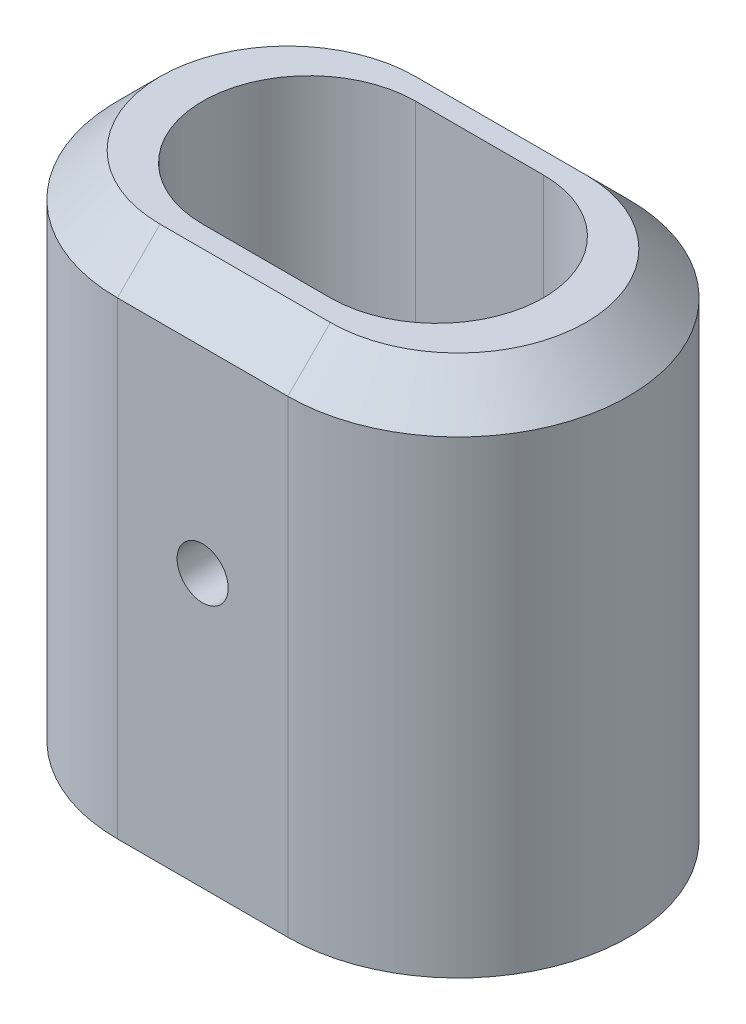
SolidWorks part; units mm, degrees
ref_plane "前基準面" through (0, 0, 0) normal (0, 0, 1) x (1, 0, 0)
ref_plane "上基準面" through (0, 0, 0) normal (0, 1, 0) x (1, 0, 0)
ref_plane "右基準面" through (0, 0, 0) normal (1, 0, 0) x (0, 0, -1)
sketch "草圖1" plane through (0, 0, 0) normal (0, 1, 0) x (1, 0, 0)
  line L0 (0, 0) -> (20, 0) construction
  line L1 (0, 20) -> (20, 20)
  line L2 (0, -20) -> (20, -20)
  arc A0 (0, 20) -> (0, -20) centre (0, 0) ccw
  arc A1 (20, -20) -> (20, 20) centre (20, 0) ccw
  point P3 (10, 0)
  dimension "D2" = 20
  dimension "D1" = 20
extrude "填料-伸長1" add sketch "草圖1" along normal blind 60
chamfer "導角1" distance 5 angle 45 4 edges at (10, 60, -20) (40, 60, 0) (10, 60, 20) (-20, 60, 0)
sketch "草圖2" plane through (0, 60, 0) normal (0, 1, 0) x (1, 0, 0)
  line L0 (2.5, 0) -> (17.5, 0) construction
  line L1 (2.5, 12.5) -> (17.5, 12.5)
  line L2 (2.5, -12.5) -> (17.5, -12.5)
  line L3 (10, -15) -> (10, 0)
  line L5 (0, -15) -> (20, -15) construction
  arc A0 (2.5, 12.5) -> (2.5, -12.5) centre (2.5, 0) ccw
  arc A1 (17.5, -12.5) -> (17.5, 12.5) centre (17.5, 0) ccw
  point P3 (10, 0)
  dimension "D1" = 25
  dimension "D2" = 15
extrude "除料-伸長1" cut sketch "草圖2" against normal blind 60
sketch "草圖3" plane through (0, 0, 20) normal (0, 0, 1) x (1, 0, 0)
  line L0 (10, 60) -> (10, 32)
  line L4 (17.5, 60) -> (2.5, 60)
  line L5 (2.5, 60) -> (2.5, 0)
  line L6 (2.5, 0) -> (17.5, 0)
  line L7 (17.5, 0) -> (17.5, 60)
  line L8 (17.5, 60) -> (2.5, 60)
  line L9 (2.5, 60) -> (2.5, 0)
  line L10 (2.5, 0) -> (17.5, 0)
  line L11 (17.5, 0) -> (17.5, 60)
  circle A0 centre (10, 32) radius 3
  dimension "D2" = 6
  dimension "D3" = 28
  dimension "D1" = 0
extrude "除料-伸長2" cut sketch "草圖3" against normal blind 60
